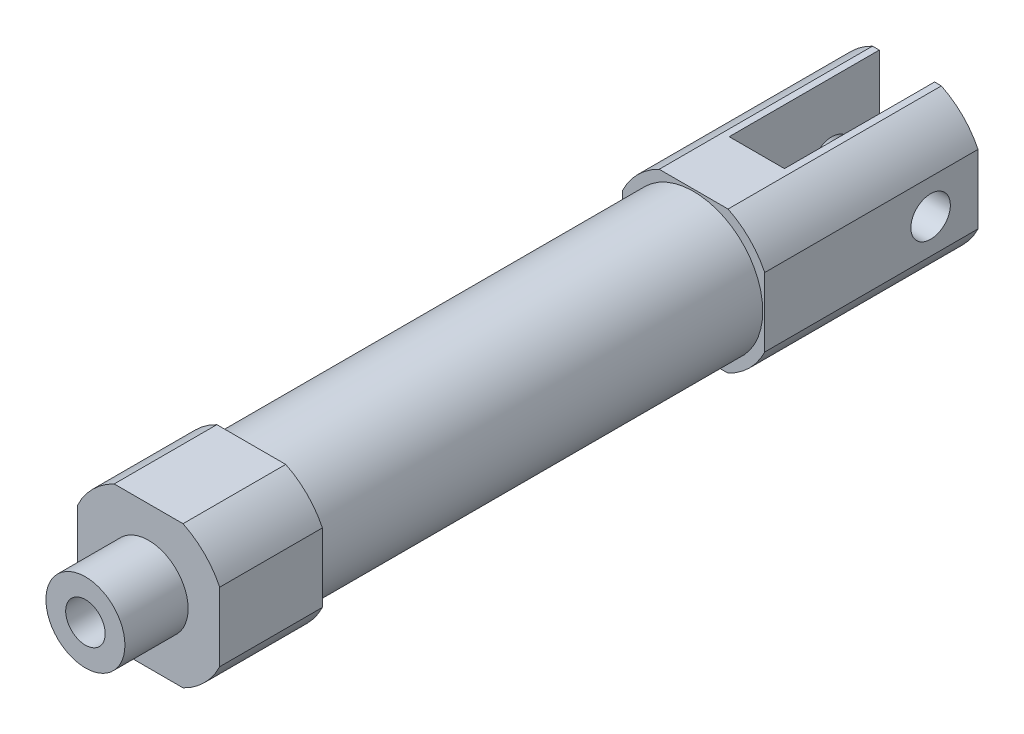
SolidWorks part; units mm, degrees
material "1060 Alloy"
ref_plane "Front Plane" through (0, 0, 0) normal (0, 0, 1) x (1, 0, 0)
ref_plane "Top Plane" through (0, 0, 0) normal (0, 1, 0) x (1, 0, 0)
ref_plane "Right Plane" through (0, 0, 0) normal (1, 0, 0) x (0, 0, -1)
sketch "Sketch1" plane through (0, 0, 0) normal (0, 0, 1) x (1, 0, 0)
  line L1 (-4.3589, -9) -> (4.3589, -9)
  line L2 (-9, -4.3589) -> (-9, 4.3589)
  line L3 (-4.3589, 9) -> (4.3589, 9)
  line L4 (9, -4.3589) -> (9, 4.3589)
  line L5 (-7.0711, -7.0711) -> (7.0711, 7.0711) construction
  line L6 (-7.0711, 7.0711) -> (7.0711, -7.0711) construction
  circle A0 centre (0, 0) radius 10
extrude "Boss-Extrude1" add sketch "Sketch1" along normal blind 27 contours L4 A0 L3 L2 L1
sketch "Sketch2" plane through (0, 0, 27) normal (0, 0, 1) x (1, 0, 0)
  circle A0 centre (0, 0) radius 8.75
extrude "Boss-Extrude2" add sketch "Sketch2" along normal blind 56
sketch "Sketch3" plane through (0, 0, 83) normal (0, 0, 1) x (1, 0, 0)
  line L1 (-4.3589, -9) -> (4.3589, -9)
  line L2 (-9, -4.3589) -> (-9, 4.3589)
  line L3 (-4.3589, 9) -> (4.3589, 9)
  line L4 (9, -4.3589) -> (9, 4.3589)
  line L5 (-7.0711, -7.0711) -> (7.0711, 7.0711) construction
  line L6 (-7.0711, 7.0711) -> (7.0711, -7.0711) construction
  circle A0 centre (0, 0) radius 10
  circle M1 centre (0, 0) radius 8.75
extrude "Boss-Extrude3" add sketch "Sketch3" along normal blind 13 contours M1 | L4 A0 L3 L2 L1 M1
sketch "Sketch4" plane through (0, 0, 96) normal (0, 0, 1) x (1, 0, 0)
  circle A0 centre (0, 0) radius 5
extrude "Boss-Extrude4" add sketch "Sketch4" along normal blind 8
sketch "Sketch6" plane through (0, 0, 104) normal (0, 0, 1) x (1, 0, 0)
  circle A0 centre (0, 0) radius 2.5
extrude "Cut-Extrude1" cut sketch "Sketch6" against normal blind 30
sketch "Sketch7" plane through (0, 9, 0) normal (0, 1, 0) x (1, 0, 0)
  line L0 (0, 0) -> (-3.5, 0)
  line L1 (-4.3589, 0) -> (4.3589, 0) construction
  line L2 (-3.5, 0) -> (-3.5, -19)
  line L3 (-3.5, -19) -> (3.5, -19)
  line L4 (3.5, -19) -> (3.5, 0)
  line L5 (3.5, 0) -> (0, 0)
extrude "Cut-Extrude2" cut sketch "Sketch7" against normal up to next
sketch "Sketch8" plane through (-9, 0, 0) normal (-1, 0, 0) x (0, 0, 1)
  line L0 (0, -4.3589) -> (0, 4.3589) construction
  circle A0 centre (6, 0) radius 2.5
  point P2 (0, 0)
  dimension "D1" = 6
extrude "Cut-Extrude3" cut sketch "Sketch8" against normal through all
